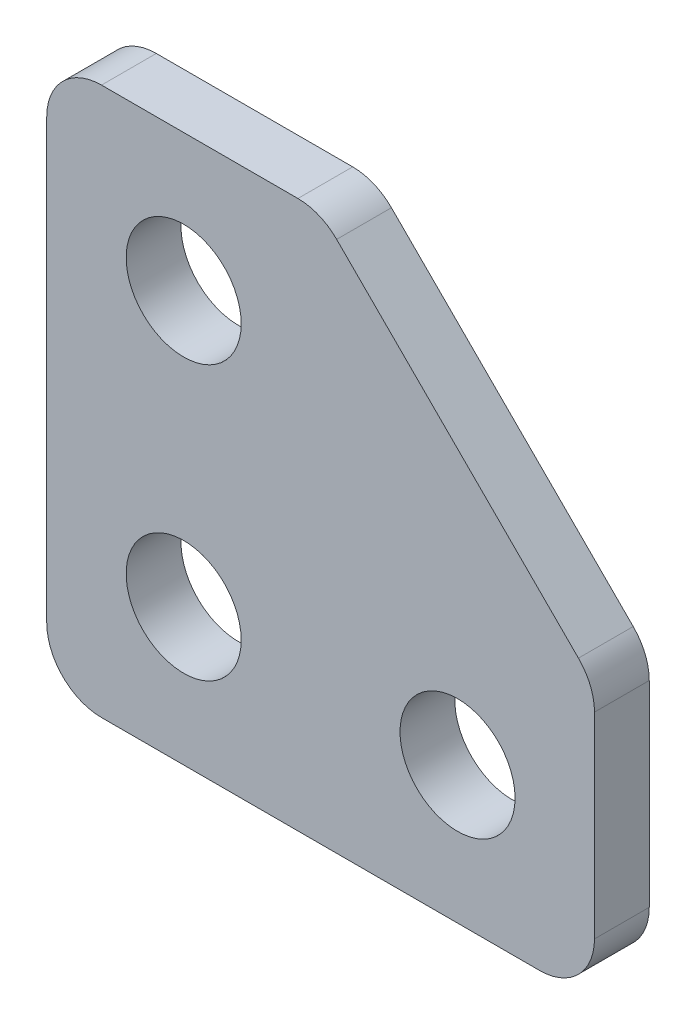
SolidWorks part; units mm, degrees
material "5052-H34"
ref_plane "正面" through (0, 0, 0) normal (0, 0, 1) x (1, 0, 0)
ref_plane "平面" through (0, 0, 0) normal (0, 1, 0) x (1, 0, 0)
ref_plane "右側面" through (0, 0, 0) normal (1, 0, 0) x (0, 0, -1)
sketch "ｽｹｯﾁ1" plane through (0, 0, 0) normal (0, 0, 1) x (1, 0, 0)
  line L0 (0, 0) -> (10, 0) construction
  line L1 (0, 0) -> (0, 10) construction
  line L2 (5, 15) -> (15, 5)
  line L3 (-5, 15) -> (5, 15)
  line L4 (-5, 15) -> (-5, -5)
  line L5 (-5, -5) -> (5, -5)
  line L6 (5, 15) -> (5, -5)
  line L7 (-5, 15) -> (5, -5) construction
  line L8 (-5, -5) -> (5, 15) construction
  line L9 (15, 5) -> (-5, 5)
  line L10 (15, 5) -> (15, -5)
  line L11 (15, -5) -> (-5, -5)
  line L12 (-5, 5) -> (-5, -5)
  line L13 (15, 5) -> (-5, -5) construction
  line L14 (15, -5) -> (-5, 5) construction
  circle A0 centre (0, 0) radius 2.1
  circle A1 centre (0, 10) radius 2.1
  circle A2 centre (10, 0) radius 2.1
  point P7 (0, 5)
  point P12 (5, 0)
  dimension "D2" = 4.2
  dimension "D1" = 10
  dimension "D3" = 10
  dimension "D4" = 10
extrude "ﾎﾞｽ - 押し出し1" add sketch "ｽｹｯﾁ1" along normal blind 2 contours L9 L6 L3 L4 A1 | L9 L2 L6 | L6 L9 L4 L5 A0 | L11 L10 L9 L6 A2
fillet "ﾌｨﾚｯﾄ1" radius 2 5 edges at (-5, -5, 1) (15, -5, 1) (15, 5, 1) (5, 15, 1) (-5, 15, 1)
